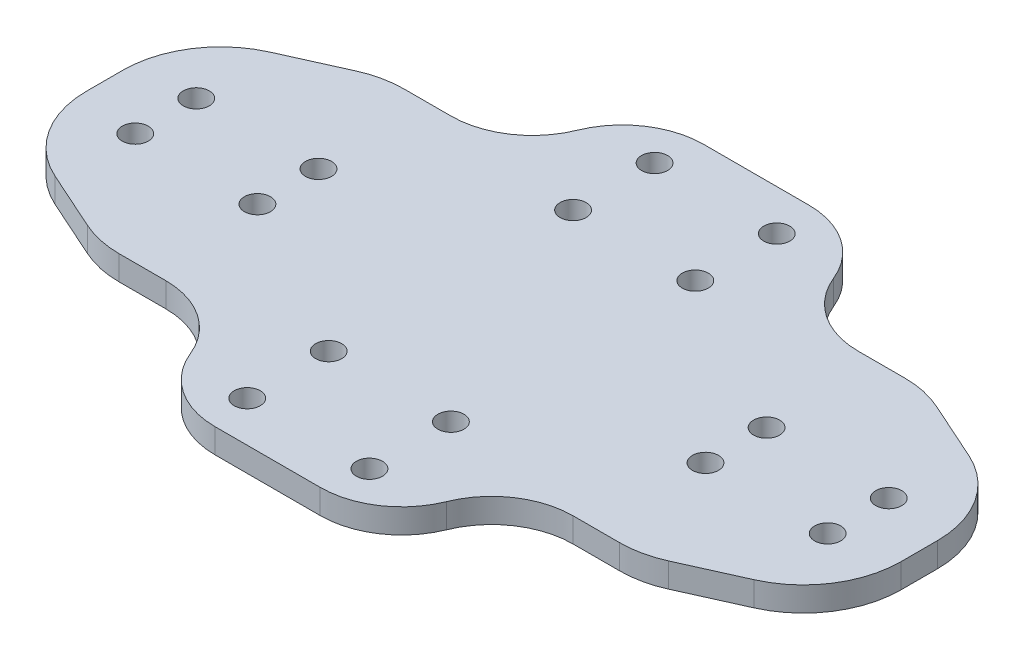
SolidWorks part; units mm, degrees
ref_plane "前视基准面" through (0, 0, 0) normal (0, 0, 1) x (1, 0, 0)
ref_plane "上视基准面" through (0, 0, 0) normal (0, 1, 0) x (1, 0, 0)
ref_plane "右视基准面" through (0, 0, 0) normal (1, 0, 0) x (0, 0, -1)
other "Configuration Table"
sketch "草图2" plane through (0, 0, 0) normal (0, 1, 0) x (1, 0, 0)
  line L0 (0, 0) -> (-9.2575, 0) construction
  line L1 (-15, -30) -> (15, -30)
  line L2 (-15, -30) -> (-15, 30)
  line L3 (-15, 30) -> (15, 30)
  line L4 (15, -30) -> (15, 30)
  line L5 (-15, -30) -> (15, 30) construction
  line L6 (-15, 30) -> (15, -30) construction
  line L7 (0, 0) -> (0, 30) construction
  line L8 (-7.5, 25) -> (-7.5, 15) construction
  line L9 (-7.5, 20) -> (-1.9073, 20) construction
  line L10 (-7.5, -20) -> (-1.9073, -20) construction
  line L11 (-7.5, -25) -> (-7.5, -15) construction
  line L12 (-15, -30) -> (15, -30)
  circle A0 centre (-7.5, 25) radius 1.6
  circle A1 centre (-7.5, 15) radius 1.6
  circle A2 centre (7.5, 25) radius 1.6
  circle A3 centre (7.5, 15) radius 1.6
  circle A4 centre (7.5, -15) radius 1.6
  circle A5 centre (7.5, -25) radius 1.6
  circle A6 centre (-7.5, -15) radius 1.6
  circle A7 centre (-7.5, -25) radius 1.6
  point P0 (0, 0)
  dimension "D3" = 3.2
  dimension "D4" = 10
  dimension "D1" = 30
  dimension "D2" = 60
  dimension "D5" = 15
  dimension "D6" = 40
extrude "凸台-拉伸1" add sketch "草图2" along normal blind 3 contours L1 L4 L3 L2 A6 A4 A3 A2 A1 A0 A5 A7
sketch "草图3" plane through (0, 0, 0) normal (0, -1, 0) x (1, 0, 0)
  line L1 (-50, -17.5) -> (50, -17.5)
  line L2 (-50, -17.5) -> (-50, 17.5)
  line L3 (-50, 17.5) -> (50, 17.5)
  line L4 (50, -17.5) -> (50, 17.5)
  line L5 (-50, -17.5) -> (50, 17.5) construction
  line L6 (-50, 17.5) -> (50, -17.5) construction
  line L7 (-14.3065, -16.7863) -> (14.3065, -16.7863)
  line L8 (-14.3065, -16.7863) -> (-14.3065, 16.7863)
  line L9 (-14.3065, 16.7863) -> (14.3065, 16.7863)
  line L10 (14.3065, -16.7863) -> (14.3065, 16.7863)
  line L11 (-14.3065, -16.7863) -> (14.3065, 16.7863) construction
  line L12 (-14.3065, 16.7863) -> (14.3065, -16.7863) construction
  point P0 (0, 0)
  point P6 (0, 0)
  dimension "D1" = 35
  dimension "D2" = 100
extrude "凸台-拉伸2" add sketch "草图3" against normal blind 3
sketch "草图4" plane through (0, 0, 0) normal (0, -1, 0) x (1, 0, 0)
  line L0 (0, 0) -> (-61.3951, 0) construction
  line L2 (-50, 10) -> (-20, 10) construction
  line L3 (-50, 10) -> (-50, -10) construction
  line L4 (-50, -10) -> (-20, -10) construction
  line L5 (-20, 10) -> (-20, -10) construction
  line L6 (-35, 10) -> (-35, -10) construction
  line L7 (0, 11.6238) -> (0, 0) construction
  circle A0 centre (-42.5, 3.75) radius 1.6
  circle A1 centre (-42.5, -3.75) radius 1.6
  circle A2 centre (-27.5, -3.75) radius 1.6
  circle A3 centre (-27.5, 3.75) radius 1.6
  circle A4 centre (42.5, 3.75) radius 1.6
  circle A5 centre (42.5, -3.75) radius 1.6
  circle A6 centre (27.5, -3.75) radius 1.6
  circle A7 centre (27.5, 3.75) radius 1.6
  dimension "D2" = 3.2
  dimension "D1" = 30
  dimension "D3" = 10
  dimension "D4" = 10
  dimension "D5" = 3.75
  dimension "D6" = 7.5
extrude "切除-拉伸1" cut sketch "草图4" against normal through all
sketch "草图6" plane through (0, 3, 0) normal (0, 1, 0) x (1, 0, 0)
  line L0 (-15, 30) -> (-23.2916, 17.5)
  line L1 (-50, 17.5) -> (-15, 17.5) construction
  line L2 (-23.2916, 17.5) -> (-33.2916, 17.5)
  line L3 (0, 0) -> (-63.6824, 0) construction
  line L5 (0, 0) -> (0, 12.5876) construction
  line L6 (-33.2916, 17.5) -> (-50, 10)
  line L7 (-50, -17.5) -> (-50, 17.5) construction
  line L8 (-50, 10) -> (-50, -10)
  line L9 (-15, 30) -> (15, 30)
  line L10 (-15, -30) -> (15, -30)
  line L11 (-33.2916, -17.5) -> (-50, -10)
  line L12 (-23.2916, -17.5) -> (-33.2916, -17.5)
  line L13 (-15, -30) -> (-23.2916, -17.5)
  line L14 (15, -30) -> (23.2916, -17.5)
  line L15 (23.2916, -17.5) -> (33.2916, -17.5)
  line L16 (33.2916, -17.5) -> (50, -10)
  line L17 (50, 10) -> (50, -10)
  line L18 (33.2916, 17.5) -> (50, 10)
  line L19 (23.2916, 17.5) -> (33.2916, 17.5)
  line L20 (15, 30) -> (23.2916, 17.5)
  point P18 (-50, 0)
  point P26 (0, -30)
  point P27 (0, 30)
  point P30 (50, 0)
  dimension "D1" = 10
  dimension "D2" = 10
  dimension "D3" = 15
extrude "切除-拉伸2" cut sketch "草图6" against normal through all flip side to cut
fillet "圆角3" radius 10 4 edges at (15, 1.5, 17.5) (-15, 1.5, 17.5) (15, 1.5, -17.5) (-15, 1.5, -17.5)
fillet "圆角4" radius 10 4 edges at (-15, 1.5, 30) (15, 1.5, 30) (15, 1.5, -30) (-15, 1.5, -30)
fillet "圆角5" radius 12 4 edges at (50, 1.5, -10) (50, 1.5, 10) (-50, 1.5, 10) (-50, 1.5, -10)
fillet "圆角6" radius 12 4 edges at (33.2916, 1.5, -17.5) (33.2916, 1.5, 17.5) (-33.2916, 1.5, 17.5) (-33.2916, 1.5, -17.5)
sketch "草图7" plane through (0, 3, 0) normal (0, 1, 0) x (1, 0, 0)
  line L0 (0, 0) -> (0, 11.2402) construction
